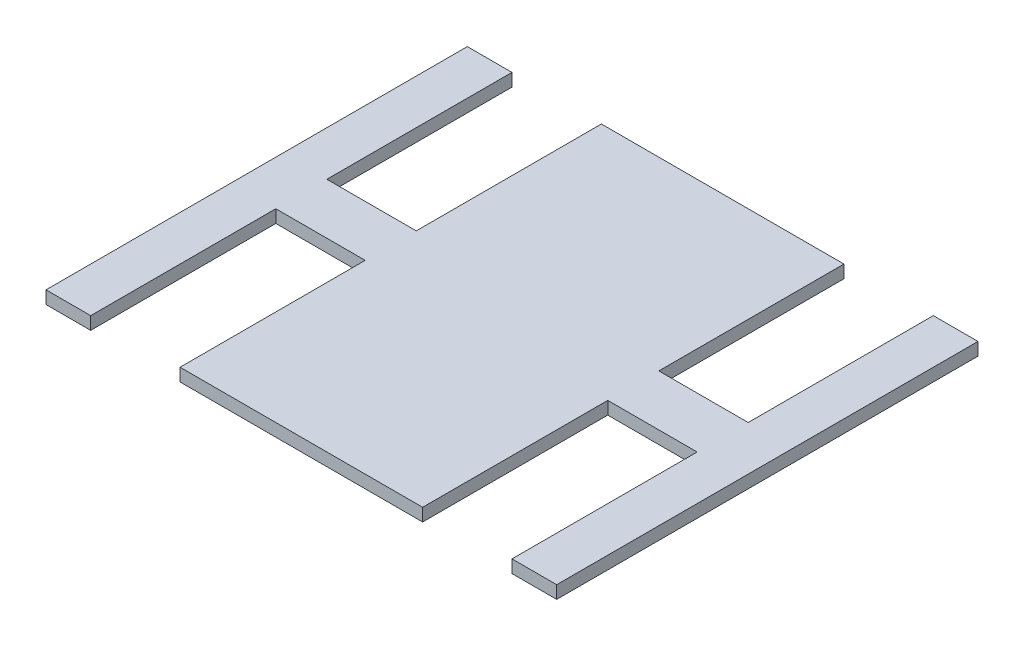
SolidWorks part; units mm, degrees
material "1060 Legierung"
ref_plane "Ebene vorne" through (0, 0, 0) normal (0, 0, 1) x (1, 0, 0)
ref_plane "Ebene oben" through (0, 0, 0) normal (0, 1, 0) x (1, 0, 0)
ref_plane "Ebene rechts" through (0, 0, 0) normal (1, 0, 0) x (0, 0, -1)
sketch "Skizze1" plane through (0, 0, 0) normal (0, 1, 0) x (1, 0, 0)
  line L1 (-200, -165) -> (200, -165)
  line L2 (-200, -165) -> (-200, 165)
  line L3 (-200, 165) -> (200, 165)
  line L4 (200, -165) -> (200, 165)
  line L5 (-200, -165) -> (200, 165) construction
  line L6 (-200, 165) -> (200, -165) construction
  line L7 (-165, 165) -> (-95, 165)
  line L8 (-165, 165) -> (-165, 20)
  line L9 (-165, 20) -> (-95, 20)
  line L10 (-95, 165) -> (-95, 20)
  line L11 (-95, -165) -> (-165, -165)
  line L12 (-95, -165) -> (-95, -20)
  line L13 (-95, -20) -> (-165, -20)
  line L14 (-165, -165) -> (-165, -20)
  line L15 (95, 165) -> (165, 165)
  line L16 (95, 165) -> (95, 20)
  line L17 (95, 20) -> (165, 20)
  line L18 (165, 165) -> (165, 20)
  line L19 (165, -165) -> (95, -165)
  line L20 (165, -165) -> (165, -20)
  line L21 (165, -20) -> (95, -20)
  line L22 (95, -165) -> (95, -20)
  point P0 (0, 0)
  point P30 (0, 0)
  point P31 (0, 0)
  dimension "D1" = 330
  dimension "D2" = 400
  dimension "D3" = 145
  dimension "D4" = 70
  dimension "D5" = 70
  dimension "D6" = 145
  dimension "D7" = 35
  dimension "D8" = 35
  dimension "D9" = 70
  dimension "D10" = 35
  dimension "D11" = 145
  dimension "D12" = 145
  dimension "D16" = 70
  dimension "D19" = 35
extrude "Aufsatz-Linear austragen1" add sketch "Skizze1" along normal blind 10
sketch "Skizze2" plane through (0, 10, 0) normal (0, 1, 0) x (1, 0, 0)
  line L0 (-95, -165) -> (-95, -20) construction
  line L10 (-75, -143.3998) -> (85, -143.3998)
  line L12 (-50, 80) -> (50, 80)
  line L13 (-50, 80) -> (-50, -53.3998)
  line L14 (-50, -53.3998) -> (50, -53.3998)
  line L15 (50, 80) -> (50, -53.3998)
  line L16 (-75, -143.3998) -> (-75, 56.6002)
  line L17 (-75, 56.6002) -> (85, 56.6002)
  line L18 (85, -143.3998) -> (85, 56.6002)
  line L21 (-85, 145) -> (95, 145)
  line L22 (-85, 145) -> (-85, 75)
  line L23 (-85, 75) -> (95, 75)
  line L24 (95, 145) -> (95, 75)
  line L25 (-95, 165) -> (-95, 20) construction
  line L26 (-95, 165) -> (95, 165) construction
  dimension "D2" = 20
  dimension "D3" = 160
  dimension "D4" = 110
  dimension "D5" = 180
  dimension "D6" = 10
  dimension "D7" = 100
  dimension "D8" = 70
  dimension "D9" = 20
  dimension "D10" = 200
  dimension "D11" = 80
